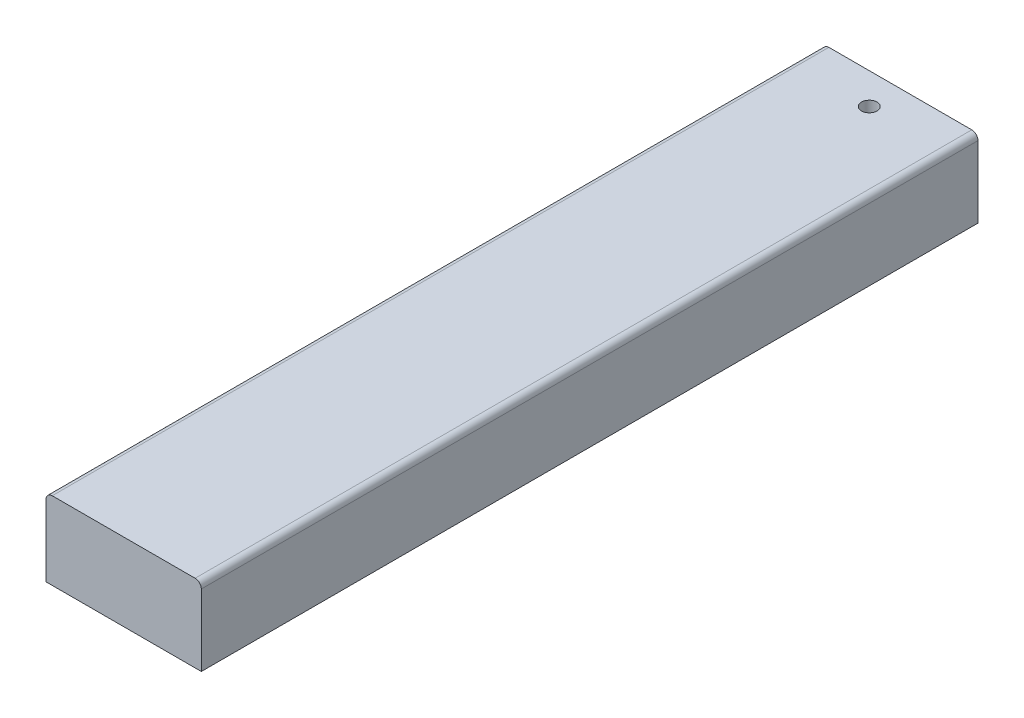
SolidWorks part; units mm, degrees
ref_plane "Front Plane" through (0, 0, 0) normal (0, 0, 1) x (1, 0, 0)
ref_plane "Top Plane" through (0, 0, 0) normal (0, 1, 0) x (1, 0, 0)
ref_plane "Right Plane" through (0, 0, 0) normal (1, 0, 0) x (0, 0, -1)
sketch "Sketch1" plane through (0, 0, 0) normal (0, 0, 1) x (1, 0, 0)
  line L1 (25, -10) -> (-25, -10)
  line L2 (25, -10) -> (25, 10)
  line L3 (25, 10) -> (-25, 10)
  line L4 (-25, -10) -> (-25, 10)
  line L5 (0, 10) -> (0, -10) construction
  line L6 (25, 0) -> (-25, 0) construction
  point P0 (0, 0)
  dimension "D1" = 20
  dimension "D2" = 50
extrude "Boss-Extrude1" add sketch "Sketch1" along normal mid plane 250
sketch "Sketch3" plane through (0, 10, 0) normal (0, 1, 0) x (1, 0, 0)
  line L0 (25, 125) -> (-25, 125) construction
  line L1 (25, 125) -> (-25, 125)
  line L2 (25, 125) -> (25, -125)
  line L3 (25, -125) -> (-25, -125)
  line L4 (-25, 125) -> (-25, -125)
  line L5 (0, -125) -> (0, 125) construction
  line L6 (25, 0) -> (-25, 0) construction
  point P0 (0, 0)
  dimension "D1" = 50
extrude "Boss-Extrude2" add sketch "Sketch3" along normal blind 5
ref_plane "Plane1" through (0, 15, 0) normal (0, 1, 0) x (1, 0, 0)
sketch "Sketch2" plane through (0, 15, 0) normal (0, 1, 0) x (1, 0, 0)
  line L1 (25, 125) -> (-25, 125) construction
  circle A0 centre (0, 115) radius 2.5
  dimension "D1" = 5
  dimension "D2" = 10
extrude "Cut-Extrude1" cut sketch "Sketch2" against normal blind 10 and the other way through all
fillet "Fillet1" radius 2 2 edges at (-25, 15, 0) (25, 15, 0)
